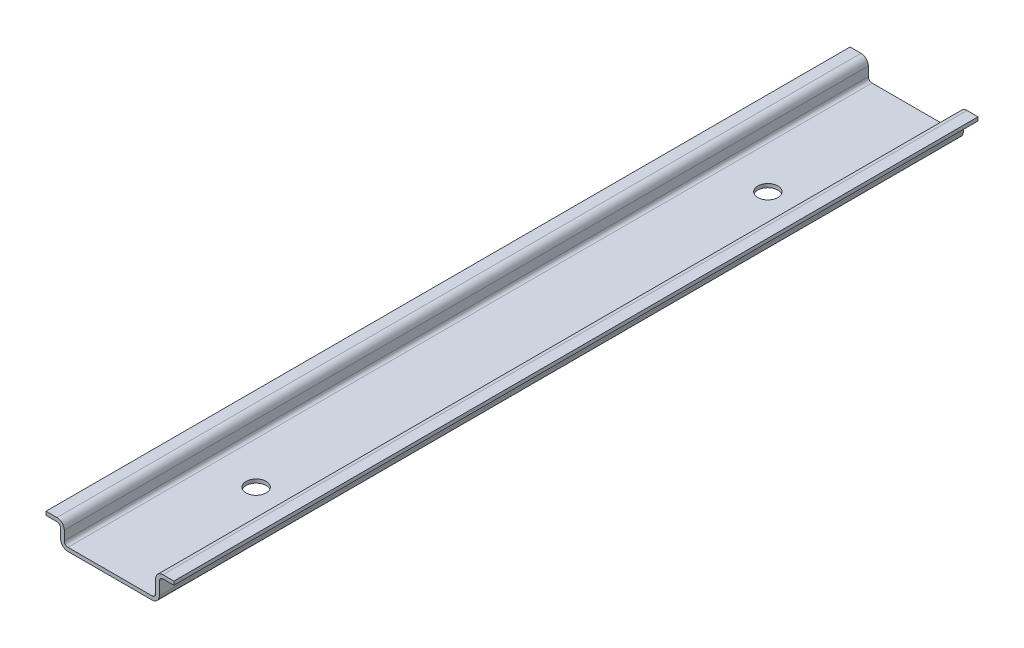
SolidWorks part; units mm, degrees
ref_plane "Front Plane" through (0, 0, 0) normal (0, 0, 1) x (1, 0, 0)
ref_plane "Top Plane" through (0, 0, 0) normal (0, 1, 0) x (1, 0, 0)
ref_plane "Right Plane" through (0, 0, 0) normal (1, 0, 0) x (0, 0, -1)
sketch "Sketch1" plane through (0, 0, 0) normal (0, 0, 1) x (1, 0, 0)
  line L0 (2, 0) -> (25, 0)
  line L1 (0, 2) -> (0, 4.5445)
  line L2 (-1, 5.5445) -> (-4, 5.5445)
  line L3 (27, 2) -> (27, 5.5)
  line L4 (28, 6.5) -> (31, 6.5)
  line L5 (-1, 6.5445) -> (-4, 6.5445)
  line L6 (1, 2) -> (1, 4.5445)
  line L7 (2, 1) -> (25, 1)
  line L8 (26, 2) -> (26, 5.5)
  line L9 (28, 7.5) -> (31, 7.5)
  line L10 (-4, 5.5445) -> (-4, 6.5445)
  line L11 (31, 6.5) -> (31, 7.5)
  line L12 (27, 0) -> (27, 6.5) construction
  line L13 (27, 6.5) -> (31, 6.5) construction
  line L14 (1, 1) -> (26, 1) construction
  line L15 (26, 1) -> (26, 7.5) construction
  line L16 (1, 1) -> (1, 6.5445) construction
  line L17 (0, 0) -> (0, 5.5445) construction
  line L18 (0, 5.5445) -> (-4, 5.5445) construction
  line L19 (26, 7.5) -> (31, 7.5) construction
  line L20 (0, 0) -> (27, 0) construction
  line L21 (1, 6.5445) -> (-4, 6.5445) construction
  arc A0 (27, 5.5) -> (28, 6.5) centre (28, 5.5) cw
  arc A1 (25, 1) -> (26, 2) centre (25, 2) ccw
  arc A2 (1, 2) -> (2, 1) centre (2, 2) ccw
  arc A3 (0, 4.5445) -> (-1, 5.5445) centre (-1, 4.5445) ccw
  arc A4 (26, 5.5) -> (28, 7.5) centre (28, 5.5) cw
  arc A5 (25, 0) -> (27, 2) centre (25, 2) ccw
  arc A6 (2, 0) -> (0, 2) centre (2, 2) cw
  arc A7 (-1, 6.5445) -> (1, 4.5445) centre (-1, 4.5445) cw
  point P16 (27, 6.5)
  point P26 (0, 5.5445)
  dimension "D7" = 1
  dimension "D8" = 2
  dimension "D2" = 4
  dimension "D3" = 4
  dimension "D5" = 7.5
  dimension "D6" = 35
  dimension "D4" = 1
extrude "Boss-Extrude1" add sketch "Sketch1" along normal blind 220
sketch "Sketch2" plane through (0, 1, 0) normal (0, 1, 0) x (1, 0, 0)
  line L0 (25, -220) -> (2, -220) construction
  line L1 (25, 0) -> (2, 0) construction
  line L3 (2, -220) -> (2, 0) construction
  circle A0 centre (13.5, -40) radius 2.75
  circle A1 centre (13.5, -180) radius 2.75
  dimension "D2" = 40
  dimension "D3" = 5.5
  dimension "D4" = 5.5
  dimension "D1" = 40
  dimension "D5" = 11.5
  dimension "D6" = 11.5
extrude "Cut-Extrude1" cut sketch "Sketch2" against normal blind 1
